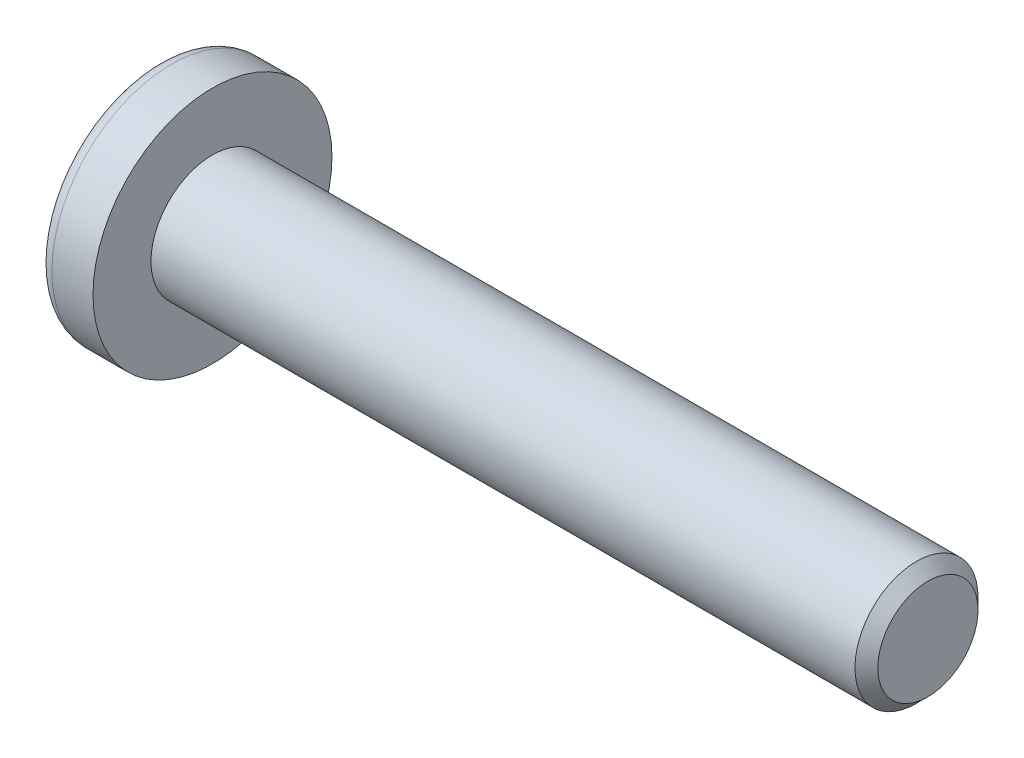
SolidWorks part; units mm, degrees
material "Alloy Steel"
ref_plane "Plane1" through (0, 0, 0) normal (0, 0, 1) x (1, 0, 0)
ref_plane "Plane2" through (0, 0, 0) normal (0, 1, 0) x (1, 0, 0)
ref_plane "Plane3" through (0, 0, 0) normal (1, 0, 0) x (0, 0, -1)
revolve "Base-Revolve" add sketch "BodySke" angle 360 about L2
sketch "BodySke" plane through (0, 0, 0) normal (0, 0, 1) x (1, 0, 0)
  line L0 (1.5748, 1.0922) -> (1.5748, 2.1209)
  line L1 (1.8021, 6.35) -> (1.8021, -3.175) construction
  line L2 (-25.4, 0) -> (127, 0) construction
  line L3 (14.2748, 0) -> (0, 0)
  line L4 (1.5748, 1.0922) -> (14.2748, 1.0922)
  line L5 (14.2748, 1.0922) -> (14.2748, 0)
  line L6 (0.8457, 2.1209) -> (1.5748, 2.1209)
  line L7 (1.5748, -1.0922) -> (14.2748, -1.0922) construction
  line L8 (1.5748, 6.35) -> (1.5748, -3.175) construction
  arc A0 (0.6381, 2.0132) -> (0, 0) centre (3.495, 0) ccw
  arc A2 (0.6381, 2.0132) -> (0.8457, 2.1209) centre (0.8457, 1.8669) cw
  dimension "Head_fillet_rad" = 0.254
  dimension "Head_crown_rad" = 3.495
  dimension "Head_ht" = 1.5748
  dimension "Diameter" = 2.1844
  dimension "Length" = 12.7
  dimension "Head_dia" = 4.2418
  dimension "Advance" = 0.4547
  dimension "Thread_nom" = 12.7
cosmetic thread "ThreadCosmetic" parameters "Thread_length"=12.2453, "Thread_minor"=1.6459
sketch "Sketch3" plane through (0, 0, 0) normal (1, 0, 0) x (0, 0, -1)
  line L0 (0.3429, -1.3843) -> (-0.3429, -1.3843)
  line L1 (0.3429, -1.3843) -> (0.3429, 1.3843)
  line L2 (-0.3429, 1.3843) -> (0.3429, 1.3843)
  line L3 (-0.3429, 1.3843) -> (-0.3429, -1.3843)
  dimension "D1" = 1.3843
  dimension "Cross_dia" = 2.7686
  dimension "D2" = 0.3429
  dimension "Cross_width" = 0.6858
ref_plane "Plane4" through (1.4986, 0, 0) normal (1, 0, 0) x (0, 0, -1)
sketch "Sketch4" plane through (1.4986, 0, 0) normal (1, 0, 0) x (0, 0, -1)
  line L0 (0.1714, -0.1715) -> (-0.1714, -0.1715)
  line L1 (0.1714, -0.1715) -> (0.1714, 0.1714)
  line L2 (-0.1714, 0.1714) -> (0.1714, 0.1714)
  line L3 (-0.1714, 0.1714) -> (-0.1714, -0.1715)
  dimension "D1" = 0.3429
  dimension "D2" = 0.3429
  dimension "D3" = 0.1714
  dimension "D4" = 0.1714
loft "Cut-Loft1" cut profiles "Sketch3", "Sketch4"
pattern_circular "CirPattern1" count 2 every 90 about axis through (0, 0, 0) along (1, 0, 0) of "Cut-Loft1"
chamfer "Chamfer1" distance 0.2032 angle 45 1 edges at (14.2748, 0, 1.0922)
equation "\"D1@Sketch3\" = \"Cross_dia@Sketch3\" / 2"
equation "\"D2@Sketch3\" = \"Cross_width@Sketch3\" / 2"
equation "\"D1@Sketch4\" = \"Cross_width@Sketch3\" *.5"
equation "\"D2@Sketch4\" = \"D1@Sketch4\""
equation "\"D3@Sketch4\" = \"D1@Sketch4\" / 2"
equation "\"D4@Sketch4\" = \"D2@Sketch4\" / 2"
equation "\"Thread_length@ThreadCosmetic\" = ((sgn( (\"Length@BodySke\" - \"Advance@BodySke\" ) - \"Thread_nom@BodySke\" )-1)*( (\"Length@BodySke\" - \"Advance@BodySke\" ) - \"Thread_nom@BodySke\" ))/-2+ \"Thread_nom@BodySke\""
